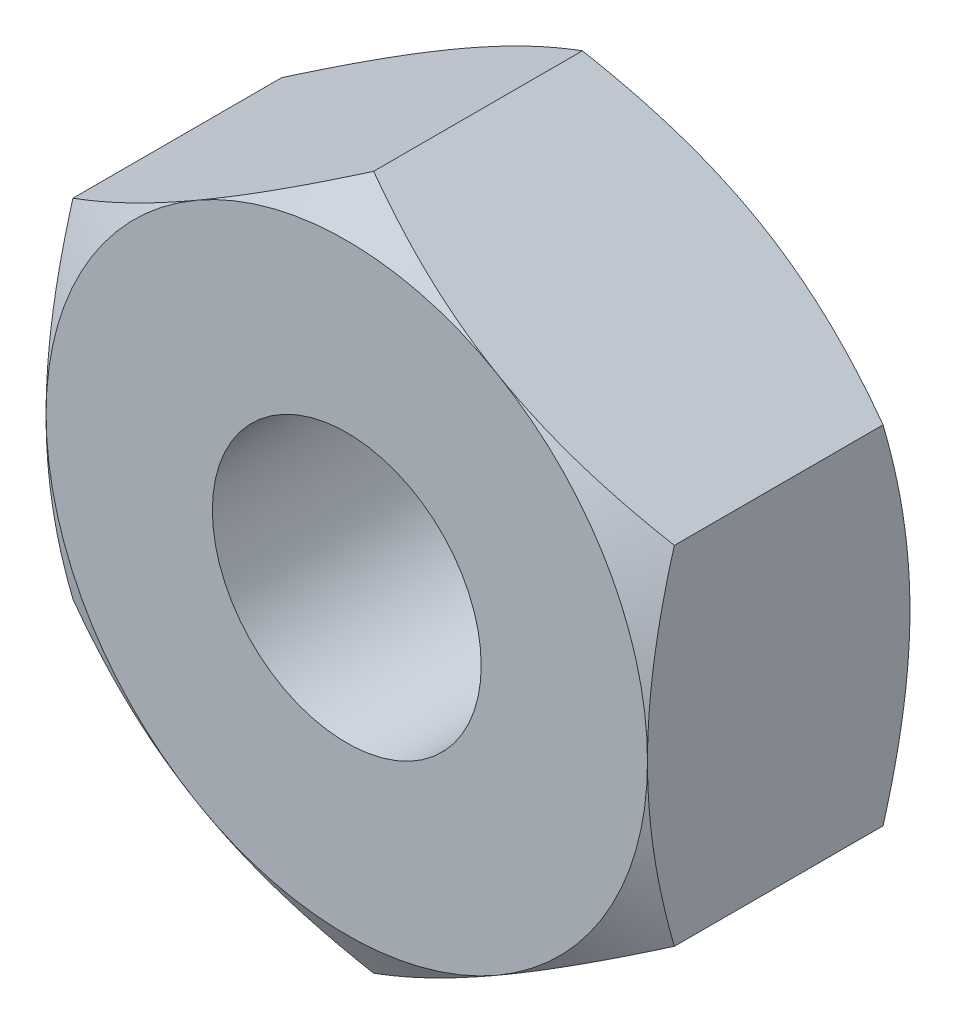
SolidWorks part; units mm, degrees
ref_plane "基准面1" through (0, 0, 0) normal (0, 0, 1) x (1, 0, 0)
ref_plane "基准面2" through (0, 0, 0) normal (0, 1, 0) x (1, 0, 0)
ref_plane "基准面3" through (0, 0, 0) normal (1, 0, 0) x (0, 0, -1)
sketch "尺寸草图" plane through (0, 0, 0) normal (0, 0, 1) x (1, 0, 0)
  line L0 (0, 0) -> (6, 0) construction
  line L1 (0, 0) -> (12, 0) construction
  line L2 (6, 0) -> (10.6, 0) construction
  line L3 (-2.8571, 0) -> (0, 0) construction
  point P3 (3, 0)
  point P4 (0.5, 0)
  point P5 (6, 0)
  point P6 (2.4, 0)
  point P8 (5.5, 0)
  dimension "D1" = 2.8571
  dimension "D" = 3
  dimension "P" = 0.5
  dimension "e(最小)" = 6
  dimension "m(最大)" = 2.4
  dimension "s(公称)" = 5.5
  dimension "dw(最小)" = 4.6
sketch "草图1" plane through (0, 0, 0) normal (0, 0, 1) x (1, 0, 0)
  line L0 (-2.75, 0) -> (2.75, 0) construction
  line L1 (0, 3.1754) -> (0, -3.1754) construction
  line L3 (0, 3.1754) -> (-2.75, 1.5877)
  line L4 (-2.75, 1.5877) -> (-2.75, -1.5877)
  line L5 (-2.75, -1.5877) -> (0, -3.1754)
  line L6 (0, -3.1754) -> (2.75, -1.5877)
  line L7 (2.75, -1.5877) -> (2.75, 1.5877)
  line L8 (2.75, 1.5877) -> (0, 3.1754)
  circle A0 centre (0, 0) radius 2.75 construction
  circle A1 centre (0, 0) radius 1.2294
  point P2 (0, 2.8246)
  dimension "D1" = 6
  dimension "D" = 2.4588
  dimension "D2" = 5.5
extrude "基体-拉伸" add sketch "草图1" along normal blind 2.4
cosmetic thread "装饰螺纹线1" parameters "D2"=3
sketch "草图2" plane through (0, 0, 0) normal (0, 0, -1) x (-1, 0, 0)
  circle A0 centre (0, 0) radius 2.75
  circle A1 centre (0, 0) radius 1.2294 construction
  dimension "s" = 5.5
extrude "切除-拉伸1" cut sketch "草图2" against normal through all draft 60 flip side to cut
sketch "草图3" plane through (0, 0, 2.4) normal (0, 0, 1) x (1, 0, 0)
  circle A0 centre (0, 0) radius 2.75
  dimension "D1" = 5.5
extrude "切除-拉伸2" cut sketch "草图3" against normal through all draft 60 flip side to cut
